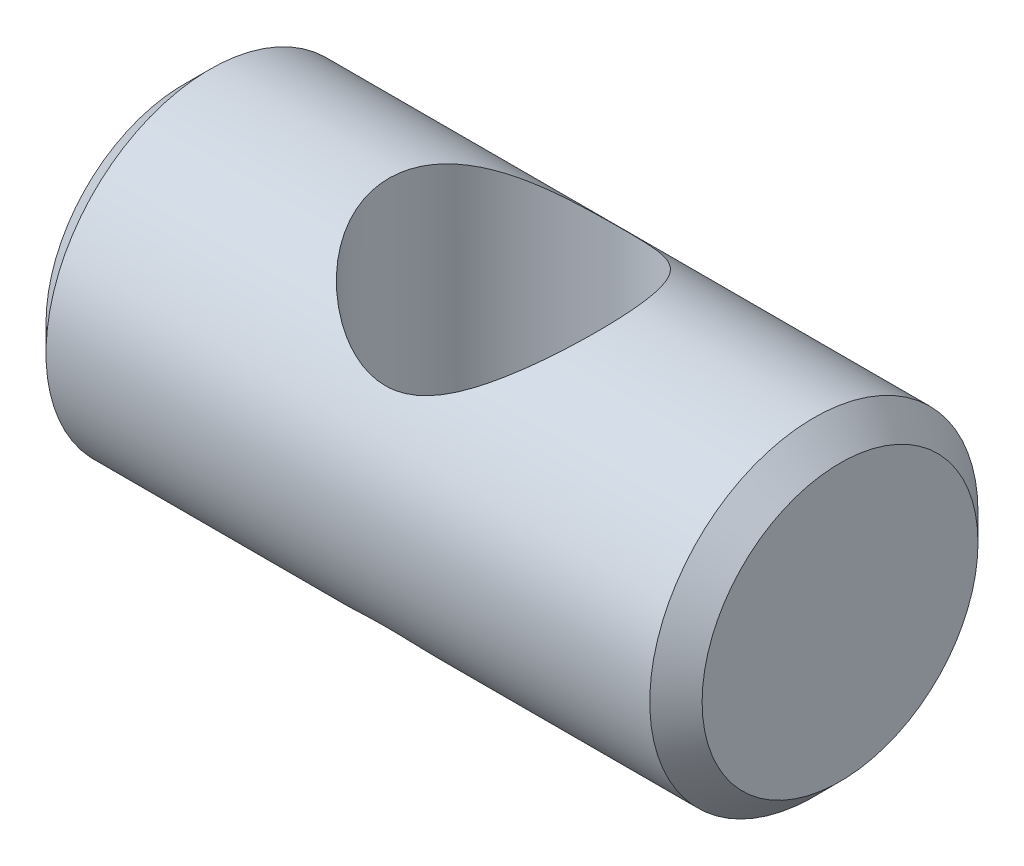
SolidWorks part; units mm, degrees
ref_plane "Front Plane" through (0, 0, 0) normal (0, 0, 1) x (1, 0, 0)
ref_plane "Top Plane" through (0, 0, 0) normal (0, 1, 0) x (1, 0, 0)
ref_plane "Right Plane" through (0, 0, 0) normal (1, 0, 0) x (0, 0, -1)
sketch "Sketch1" plane through (0, 0, 0) normal (1, 0, 0) x (0, 0, -1)
  circle A0 centre (0, 0) radius 4.765
  dimension "D1" = 9.53
extrude "Boss-Extrude1" add sketch "Sketch1" along normal mid plane 19.05
chamfer "Chamfer1" distance 0.76 angle 45 2 edges at (-9.525, 0, -4.765) (9.525, 0, -4.765)
sketch "Sketch2" plane through (0, 0, 0) normal (0, 1, 0) x (1, 0, 0)
  circle A0 centre (0, -0.25) radius 3.43
  dimension "D1" = 6.86
  dimension "D2" = 0.25
extrude "Cut-Extrude1" cut sketch "Sketch2" against normal mid plane 44.05
